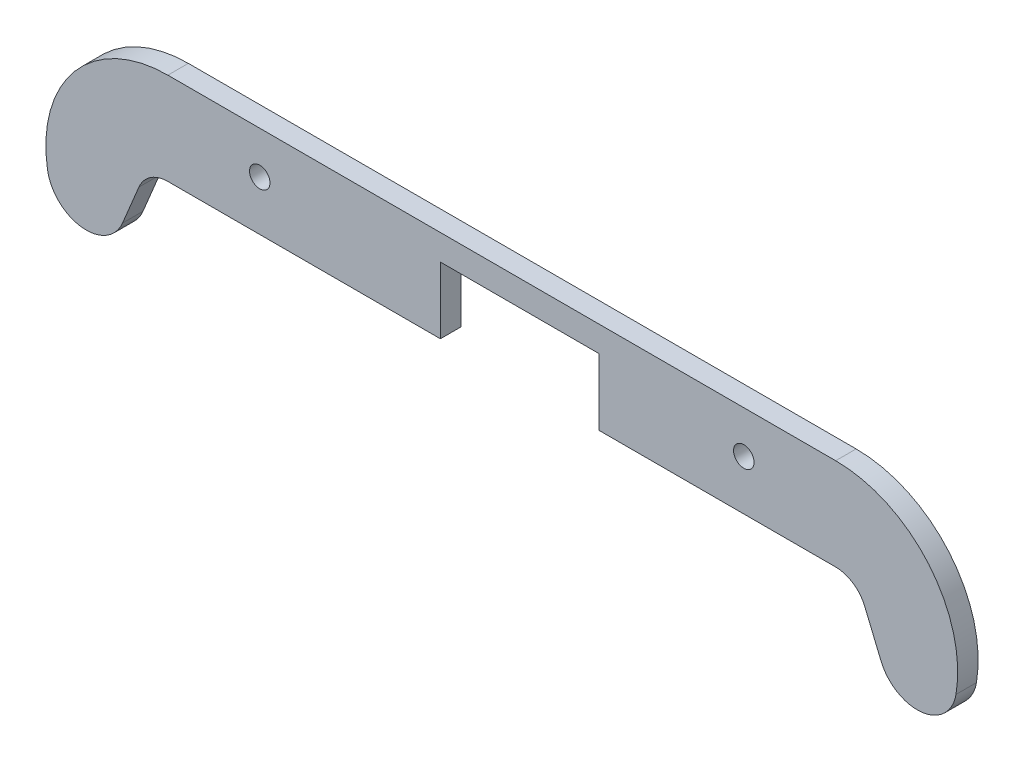
SolidWorks part; units mm, degrees
ref_plane "Front Plane" through (0, 0, 0) normal (0, 0, 1) x (1, 0, 0)
ref_plane "Top Plane" through (0, 0, 0) normal (0, 1, 0) x (1, 0, 0)
ref_plane "Right Plane" through (0, 0, 0) normal (1, 0, 0) x (0, 0, -1)
sketch "Sketch1" plane through (0, 0, 0) normal (0, 0, 1) x (1, 0, 0)
  line L0 (0, 200.9143) -> (0, -140.7937) construction
  line L1 (-210.6349, 0) -> (217.619, 0) construction
  line L2 (50, 140.7946) -> (-50, 140.7946)
  line L4 (-50.7073, 122.7946) -> (-42.5, 122.7946)
  line L6 (-42.5, 22.7946) -> (-74.161, 22.7946)
  line L7 (-85, 22.3446) -> (-85, -51.4566)
  line L8 (-76.4382, -57.2054) -> (76.4382, -57.2054)
  line L9 (0, -57.2054) -> (0, 140.7946)
  line L10 (85, 22.3446) -> (85, -51.4566)
  line L13 (50.7073, 122.7946) -> (42.5, 122.7946)
  line L15 (-50, 140.7946) -> (-65.2939, 140.7946)
  line L16 (-74.161, 111.3055) -> (-70.9654, 118.9965)
  line L17 (-65.2744, 122.7946) -> (-50.7073, 122.7946)
  line L18 (65.2744, 122.7946) -> (50.7073, 122.7946)
  line L19 (74.161, 111.3055) -> (70.9654, 118.9965)
  line L20 (50, 140.7946) -> (65.2939, 140.7946)
  line L21 (-85, 22.3446) -> (-37.5, 95.9981)
  line L22 (-74.161, 22.7946) -> (-37.5, 79.6411)
  line L23 (74.161, 22.7946) -> (37.5, 79.6411)
  line L24 (85, 22.3446) -> (37.5, 95.9981)
  line L25 (-37.5, 79.6411) -> (-37.5, 27.7946)
  line L26 (37.5, 79.6411) -> (37.5, 27.7946)
  line L27 (74.161, 22.7946) -> (42.5, 22.7946)
  line L28 (-85, -51.4566) -> (-76.4382, -57.2054)
  line L29 (85, -51.4566) -> (76.4382, -57.2054)
  line L30 (-42.5, 122.7946) -> (42.5, 122.7946)
  arc A0 (-65.2939, 140.7946) -> (-88.823, 112.9782) centre (-65.2939, 116.9351) ccw
  arc A1 (-88.823, 112.9782) -> (-74.161, 111.3055) centre (-81.2513, 114.2515) ccw
  arc A2 (-70.9654, 118.9965) -> (-65.2744, 122.7946) centre (-65.2744, 116.6319) cw
  arc A3 (70.9654, 118.9965) -> (65.2744, 122.7946) centre (65.2744, 116.6319) ccw
  arc A4 (88.823, 112.9782) -> (74.161, 111.3055) centre (81.2513, 114.2515) cw
  arc A5 (65.2939, 140.7946) -> (88.823, 112.9782) centre (65.2939, 116.9351) cw
  arc A8 (-37.5, 27.7946) -> (-42.5, 22.7946) centre (-42.5, 27.7946) cw
  arc A9 (37.5, 27.7946) -> (42.5, 22.7946) centre (42.5, 27.7946) ccw
  point P43 (-37.5, 122.7946)
  point P46 (37.5, 122.7946)
  point P49 (-37.5, 22.7946)
  point P52 (37.5, 22.7946)
  dimension "D10" = 5
  dimension "D11" = 5
  dimension "D1" = 118
  dimension "D3" = 85
  dimension "D4" = 50
  dimension "D5" = 18
  dimension "D7" = 36.661
extrude "Boss-Extrude1" add sketch "Sketch1" along normal blind 4
sketch "Sketch3" plane through (0, 0, 4) normal (0, 0, 1) x (1, 0, 0)
  line L0 (0, -68.1919) -> (0, 197.0744) construction
  line L3 (0, 137.2085) -> (0, 125.2085)
  circle A0 centre (-47.3247, 132.5348) radius 2
  circle A1 centre (47.3247, 132.5348) radius 2
extrude "Cut-Extrude1" cut sketch "Sketch3" against normal blind 10 contours A0 | A1
sketch "Sketch4" plane through (0, 0, 4) normal (0, 0, 1) x (1, 0, 0)
  line L0 (65.2939, 140.7946) -> (-65.2939, 140.7946) construction
  line L1 (-37.9997, 140.7946) -> (38.0003, 140.7946)
  line L2 (-37.9997, 140.7946) -> (-37.9997, 126.7946)
  line L3 (-37.9997, 126.7946) -> (-11.9997, 126.7946)
  line L4 (38.0003, 140.7946) -> (38.0003, 126.7946)
  line L5 (19.0003, 126.7946) -> (38.0003, 126.7946)
  line L7 (-11.9997, 126.7946) -> (-11.9997, 135.7946)
  line L8 (-11.9997, 135.7946) -> (19.0003, 135.7946)
  line L9 (19.0003, 126.7946) -> (19.0003, 135.7946)
  line L10 (-65.2744, 122.7946) -> (65.2744, 122.7946) construction
  line L11 (-11.9997, 135.7946) -> (19.0003, 135.7946)
  line L12 (-11.9997, 135.7946) -> (-11.9997, 122.7946)
  line L13 (-11.9997, 122.7946) -> (19.0003, 122.7946)
  line L14 (19.0003, 135.7946) -> (19.0003, 122.7946)
  circle A2 centre (-47.3247, 132.5348) radius 2 construction
  line M9 (-65.2744, 122.7946) -> (65.2744, 122.7946)
  dimension "D3" = 9.325
  dimension "D1" = 76
  dimension "D2" = 14
  dimension "D4" = 9
  dimension "D5" = 31
  dimension "D6" = 26
extrude "Cut-Extrude2" cut sketch "Sketch4" against normal through all contours L14 L9 L8 L7 L12 M9
